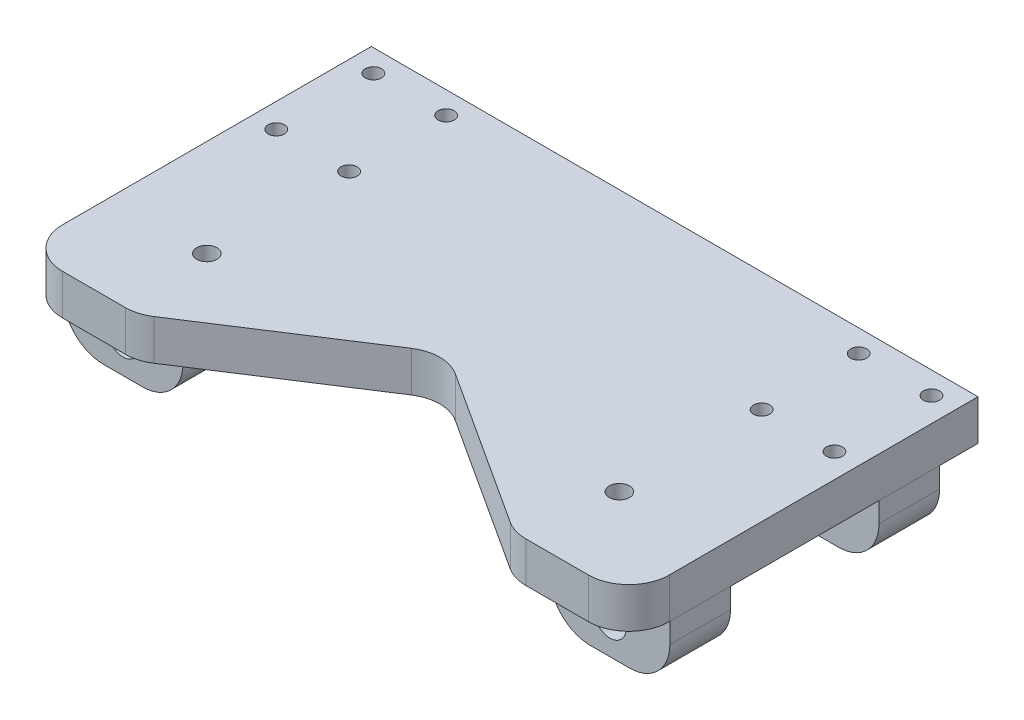
SolidWorks part; units mm, degrees
ref_plane "Front Plane" through (0, 0, 0) normal (0, 0, 1) x (1, 0, 0)
ref_plane "Top Plane" through (0, 0, 0) normal (0, 1, 0) x (1, 0, 0)
ref_plane "Right Plane" through (0, 0, 0) normal (1, 0, 0) x (0, 0, -1)
sketch "Sketch3" plane through (0, 0, 0) normal (0, 1, 0) x (1, 0, 0)
  line L0 (75.4469, -0.5285) -> (-74.5531, -0.5285) construction
  line L2 (-74.5531, -18.0285) -> (-74.5531, 16.9715)
  line L3 (-74.5531, 16.9715) -> (75.4469, 16.9715)
  line L4 (75.4469, -18.0285) -> (75.4469, 16.9715)
  line L5 (0.4469, -39.1916) -> (0.4469, 16.9715) construction
  line L7 (-68.5531, 11.4715) -> (-50.5531, 11.4715) construction
  line L8 (-68.5531, 11.4715) -> (-68.5531, -12.5285) construction
  line L9 (-68.5531, -12.5285) -> (-50.5531, -12.5285) construction
  line L10 (-50.5531, 11.4715) -> (-50.5531, -12.5285) construction
  line L11 (-68.5531, 11.4715) -> (-50.5531, -12.5285) construction
  line L12 (-68.5531, -12.5285) -> (-50.5531, 11.4715) construction
  line L19 (-74.5531, -18.0285) -> (-74.5531, -59.3519)
  line L20 (-64.5531, -69.3519) -> (-49.0669, -69.3519)
  line L23 (-43.63, -67.7448) -> (-4.99, -42.7137)
  line L24 (75.4469, -18.0285) -> (75.4469, -59.3519)
  line L25 (65.4469, -69.3519) -> (49.9607, -69.3519)
  line L26 (44.5238, -67.7448) -> (5.8838, -42.7137)
  circle A0 centre (-68.5531, 11.4715) radius 2
  circle A1 centre (-50.5531, 11.4715) radius 2
  circle A2 centre (-68.5531, -12.5285) radius 2
  circle A3 centre (-50.5531, -12.5285) radius 2
  circle A4 centre (51.4469, -12.5285) radius 2
  circle A5 centre (69.4469, -12.5285) radius 2
  circle A6 centre (69.4469, 11.4715) radius 2
  circle A7 centre (51.4469, 11.4715) radius 2
  arc A8 (75.4469, -59.3519) -> (65.4469, -69.3519) centre (65.4469, -59.3519) cw
  arc A9 (49.9607, -69.3519) -> (44.5238, -67.7448) centre (49.9607, -59.3519) cw
  arc A10 (-74.5531, -59.3519) -> (-64.5531, -69.3519) centre (-64.5531, -59.3519) ccw
  arc A11 (-49.0669, -69.3519) -> (-43.63, -67.7448) centre (-49.0669, -59.3519) ccw
  arc A12 (5.8838, -42.7137) -> (-4.99, -42.7137) centre (0.4469, -51.1065) ccw
  circle A13 centre (-50.5531, -47.6933) radius 2.5
  circle A14 centre (51.4469, -47.6933) radius 2.5
  point P0 (0, 0)
  point P6 (-59.5531, -0.5285)
  point P33 (75.4469, -69.3519)
  point P36 (47.0047, -69.3519)
  point P39 (-74.5531, -69.3519)
  point P42 (-46.1109, -69.3519)
  point P50 (-59.561, -30.7635)
  point P51 (-59.561, -32.5232)
  point P52 (-59.5531, -51.1065)
  point P53 (-50.5531, -42.7137)
  point P54 (-50.5531, -47.6933)
  dimension "D5" = 15
  dimension "D6" = 10
  dimension "D1" = 150
  dimension "D2" = 35
  dimension "D3" = 24
  dimension "D4" = 18
extrude "Boss-Extrude3" add sketch "Sketch3" along normal blind 10
sketch "Sketch4" plane through (0, 0, 0) normal (0, -1, 0) x (1, 0, 0)
  line L0 (-74.5531, 25.8566) -> (75.4469, 25.8566) construction
  line L1 (-74.5531, -7.5) -> (-44.9311, -7.5)
  line L2 (-74.5531, -7.5) -> (-74.5531, 7.5)
  line L3 (-74.5531, 7.5) -> (-44.9311, 7.5)
  line L4 (-44.9311, -7.5) -> (-44.9311, 7.5)
  line L5 (-74.5531, -7.5) -> (-44.9311, 7.5) construction
  line L6 (-74.5531, 7.5) -> (-44.9311, -7.5) construction
  line L7 (-74.5531, -16.9715) -> (-74.5531, 59.3519) construction
  line L8 (75.4469, -16.9715) -> (-74.5531, -16.9715) construction
  line L9 (-74.5531, -16.9715) -> (-74.5531, 59.3519) construction
  line L10 (-74.5531, 0) -> (75.4469, 0) construction
  line L11 (75.4469, 59.3519) -> (75.4469, -16.9715) construction
  line L12 (75.439, 7.5) -> (45.8091, 7.5)
  line L13 (45.8091, -7.5) -> (45.8091, 7.5)
  line L14 (75.439, -7.5) -> (45.8091, -7.5)
  line L15 (75.439, -7.5) -> (75.439, 7.5)
  line L16 (0.439, -16.9715) -> (0.439, 47.9553) construction
  line L17 (75.4469, 59.3519) -> (75.4469, -16.9715) construction
  line L18 (75.439, 59.2132) -> (75.439, 44.2132)
  line L19 (75.439, 59.2132) -> (45.8091, 59.2132)
  line L20 (45.8091, 59.2132) -> (45.8091, 44.2132)
  line L21 (75.439, 44.2132) -> (45.8091, 44.2132)
  line L22 (-74.5531, 44.2132) -> (-44.9311, 44.2132)
  line L23 (-44.9311, 59.2132) -> (-44.9311, 44.2132)
  line L24 (-74.5531, 59.2132) -> (-44.9311, 59.2132)
  line L25 (-74.5531, 59.2132) -> (-74.5531, 44.2132)
  point P0 (-59.7421, 0)
  dimension "D1" = 15
extrude "Boss-Extrude4" add sketch "Sketch4" along normal blind 15
fillet "Fillet1" radius 10 4 edges at (75.439, -15, 0) (45.8091, -15, 0) (-44.9311, -15, 0) (-74.5531, -15, 0)
sketch "Sketch5" plane through (0, 0, 7.5) normal (0, 0, 1) x (1, 0, 0)
  line L0 (-74.5531, -7.004) -> (-44.9311, -7.004) construction
  line L1 (-74.5531, -5) -> (-74.5531, 0) construction
  line L2 (-44.9311, -5) -> (-44.9311, 0) construction
  line L3 (0.439, 10) -> (0.439, -16.9448) construction
  circle A0 centre (-59.7421, -7.004) radius 4
  circle A1 centre (60.6201, -7.004) radius 4
extrude "Cut-Extrude1" cut sketch "Sketch5" against normal blind 15 and the other way blind 57
fillet "Fillet3" radius 10 4 edges at (75.439, -15, 51.7132) (45.8091, -15, 51.7132) (-44.9311, -15, 51.7132) (-74.5531, -15, 51.7132)
sketch "Sketch7" plane through (0, 10, 0) normal (0, 1, 0) x (1, 0, 0)
  line L0 (-50.5531, -47.6933) -> (-26.0996, -31.8523) construction
  line L1 (-50.5531, -47.6933) -> (-66.463, -31.7834) construction
  line L2 (-50.5531, -47.6933) -> (-66.3034, -63.4436) construction
  line L3 (-43.63, -67.7448) -> (-4.99, -42.7137) construction
  circle A0 centre (-66.463, -31.7834) radius 2.25
  circle A1 centre (-26.0996, -31.8523) radius 2.25
  circle A2 centre (-66.3034, -63.4436) radius 2.25
  point P8 (-26.1444, -31.7834)
  point P11 (-68.1274, -62.2558)
  point P12 (-68.3182, -64.5109)
  point P13 (-66.463, -63.4942)
  point P14 (0, 0)
  point P15 (-66.463, -63.2824)
  point P16 (-67.9352, -62.5552)
